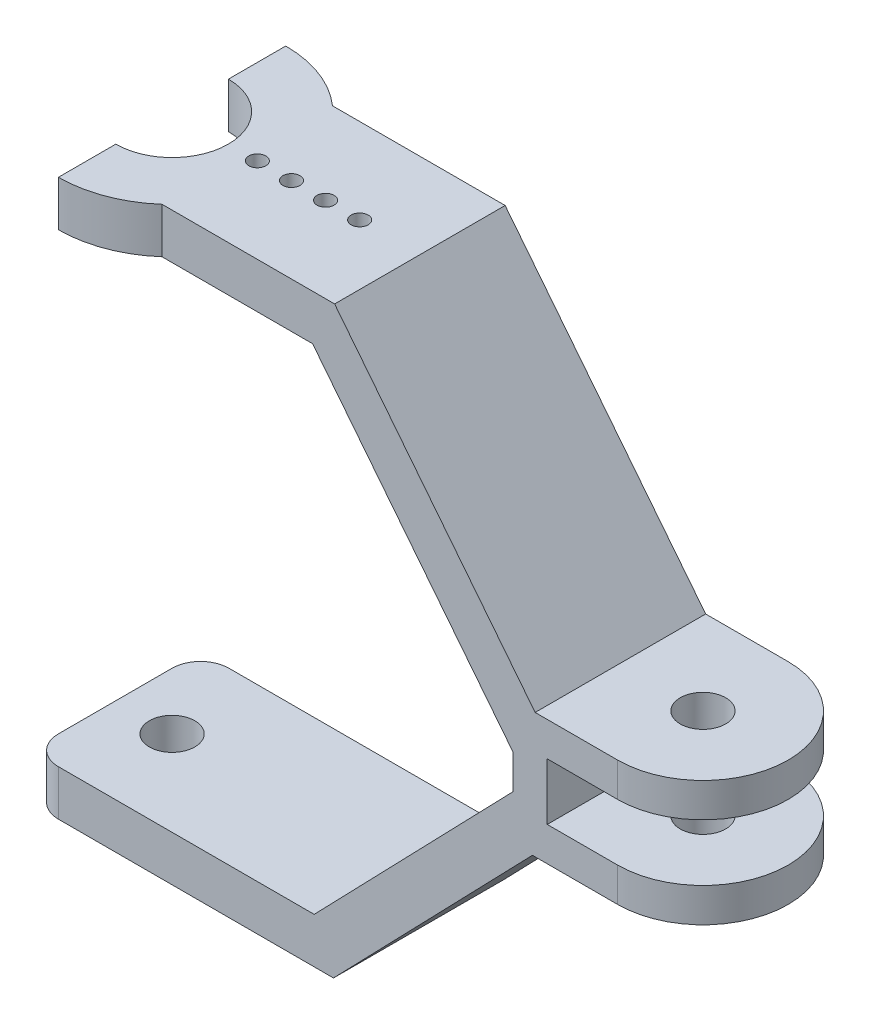
SolidWorks part; units mm, degrees
ref_plane "前基準面" through (0, 0, 0) normal (0, 0, 1) x (1, 0, 0)
ref_plane "上基準面" through (0, 0, 0) normal (0, 1, 0) x (1, 0, 0)
ref_plane "右基準面" through (0, 0, 0) normal (1, 0, 0) x (0, 0, -1)
sketch "草圖1" plane through (0, 0, 0) normal (0, 0, 1) x (1, 0, 0)
  line L0 (-24.8988, 51.4) -> (-7.2603, 29.1)
  line L1 (-25, 0) -> (-51.6965, 0)
  line L2 (0, 18.1) -> (0, 21.1)
  line L3 (-24.8988, 51.4) -> (-41.7465, 51.4)
  line L4 (-51.6965, 0) -> (-51.6965, 4)
  line L5 (-16.9816, 34.9426) -> (-9.1965, 25.1)
  line L6 (-7.5, 18.1) -> (-25, 0)
  line L7 (-7.2603, 29.1) -> (0, 29.1)
  line L8 (-7.5, 18.1) -> (0, 18.1)
  line L9 (0, 26.1) -> (0, 29.1)
  line L10 (-26.6965, 4) -> (-47.6965, 4)
  line L11 (-9.1965, 22.1) -> (-26.6965, 4)
  line L13 (0, 26.1) -> (-6.1965, 26.1)
  line L14 (-51.6965, 4) -> (-47.6965, 4)
  line L15 (-41.7465, 47.4) -> (-26.8349, 47.4)
  line L16 (-9.1965, 25.1) -> (-9.1965, 22.1)
  line L17 (-16.9816, 34.9426) -> (-26.8349, 47.4)
  line L18 (-9.1965, 22.1) -> (-4, 22.1) construction
  line L19 (-9.1965, 25.1) -> (-4, 25.1) construction
  line L20 (-4, 22.1) -> (-4, 25.1) construction
  line L21 (-47.6965, 4) -> (-47.6965, 47.4) construction
  line L22 (-51.6965, 0) -> (-51.6965, 51.4) construction
  line L23 (-41.7465, 47.4) -> (-41.7465, 51.4)
  line L24 (0, 21.1) -> (-6.1965, 21.1)
  line L25 (-6.1965, 26.1) -> (-6.1965, 21.1)
  line L26 (0, 18.1) -> (0, 29.1) construction
  line L27 (-24.8988, 51.4) -> (-7.2603, 29.1) construction
  line L28 (-26.8349, 47.4) -> (-9.1965, 25.1) construction
  line L29 (-26.8349, 47.4) -> (-47.6965, 47.4) construction
  line L30 (-24.8988, 51.4) -> (-51.6965, 51.4) construction
  dimension "D4" = 43.4
  dimension "D5" = 17.6384
  dimension "D1" = 25
  dimension "D2" = 4
  dimension "D3" = 14.9116
  dimension "D6" = 4
  dimension "D7" = 3
  dimension "D8" = 3
  dimension "D9" = 3
extrude "填料-伸長1" add sketch "草圖1" along normal blind 15
sketch "草圖2" plane through (0, 0, 0) normal (0, -1, 0) x (1, 0, 0)
  line L0 (-51.6965, 15) -> (-51.6965, 0) construction
  line L1 (-51.6965, 15) -> (-25, 15) construction
  circle A0 centre (-46.6965, 7.5) radius 2
  dimension "D1" = 5
  dimension "D2" = 7.5
  dimension "D3" = 4
extrude "除料-伸長1" cut sketch "草圖2" against normal up to surface (4 mm away) up to face at (-39.1965, 4, 7.5)
sketch "草圖3" plane through (0, 18.1, 0) normal (0, -1, 0) x (1, 0, 0)
  line L0 (0, 15) -> (0, 0) construction
  circle A0 centre (0, 7.5) radius 7.5
extrude "填料-伸長2" add sketch "草圖3" against normal blind 3
sketch "草圖4" plane through (0, 29.1, 0) normal (0, 1, 0) x (1, 0, 0)
  line L0 (0, -15) -> (0, 0) construction
  circle A0 centre (0, -7.5) radius 7.5
extrude "填料-伸長3" add sketch "草圖4" against normal blind 3
sketch "草圖5" plane through (0, 29.1, 0) normal (0, 1, 0) x (1, 0, 0)
  circle A0 centre (0, -7.5) radius 2
  dimension "D1" = 4
extrude "除料-伸長2" cut sketch "草圖5" against normal blind 11
sketch "草圖7" plane through (0, 51.4, 0) normal (0, 1, 0) x (1, 0, 0)
  line L0 (-41.7465, -15) -> (-41.7465, 0) construction
  line L1 (-26.6965, -15) -> (-51.6965, -15) construction
  line L2 (-46.6965, 2.5) -> (-46.6965, -2.55)
  line L3 (-46.6965, -12.45) -> (-46.6965, -17.5)
  arc A0 (-46.6965, -12.45) -> (-46.6965, -2.55) centre (-46.6965, -7.5) ccw
  arc A1 (-46.6965, -17.5) -> (-46.6965, 2.5) centre (-46.6965, -7.5) ccw
  dimension "D1" = 9.9
  dimension "D2" = 7.5
  dimension "D3" = 20
extrude "填料-伸長4" add sketch "草圖7" against normal up to surface (4 mm away) up to face at (-34.2907, 47.4, 7.5)
sketch "草圖6" plane through (0, 51.4, 0) normal (0, 1, 0) x (1, 0, 0)
  line L0 (-24.8988, 0) -> (-40.0821, 0) construction
  circle A0 centre (-39.1965, -7.5) radius 0.75
  circle A1 centre (-36.1965, -7.5) radius 0.75
  circle A2 centre (-33.1965, -7.5) radius 0.75
  circle A3 centre (-30.1965, -7.5) radius 0.75
  arc A4 (-46.6965, -12.45) -> (-46.6965, -2.55) centre (-46.6965, -7.5) ccw construction
  dimension "D1" = 7.5
  dimension "D2" = 7.5
  dimension "D3" = 1.5
  dimension "D4" = 3
  dimension "D5" = 3
  dimension "D6" = 3
extrude "除料-伸長3" cut sketch "草圖6" against normal blind 3
fillet "圓角1" radius 2.5 2 edges at (-51.6965, 2, 15) (-51.6965, 2, 0)
